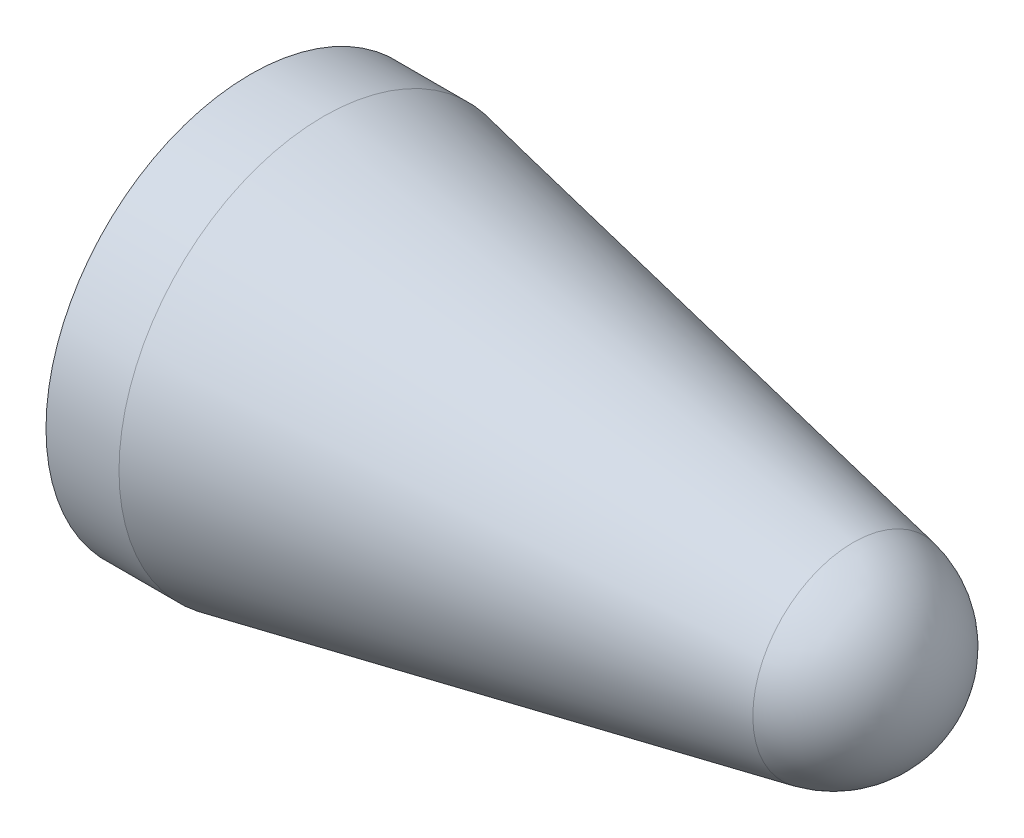
SolidWorks part; units mm, degrees
ref_plane "Front" through (0, 0, 0) normal (0, 0, 1) x (1, 0, 0)
ref_plane "Top" through (0, 0, 0) normal (0, 1, 0) x (1, 0, 0)
ref_plane "Right" through (0, 0, 0) normal (1, 0, 0) x (0, 0, -1)
sketch "Sketch1" plane through (0, 0, 0) normal (0, 0, 1) x (1, 0, 0)
  line L0 (-2, 0) -> (33, 0) construction
  line L1 (-2, 13) -> (34.1581, 5.8872)
  line L2 (-15, 1.7725) -> (-5, 11.953) construction
  line L4 (-15, 0) -> (-14, 0) construction
  line L9 (-15, 0) -> (-15, 1.7725) construction
  line L10 (-24, 16) -> (-24, 20)
  line L12 (-15, 0) -> (-17, 0) construction
  line L14 (-24, 16) -> (-17.2505, 16)
  line L25 (-14, 0) -> (-13, 0) construction
  line L26 (-13, 0) -> (-12, 0) construction
  line L27 (-12, 0) -> (-11, 0) construction
  line L28 (-11, 0) -> (-10, 0) construction
  line L29 (-10, 0) -> (-9, 0) construction
  line L30 (-14, 0) -> (-14, 2.7905) construction
  line L31 (-13, 0) -> (-13, 3.8085) construction
  line L32 (-17, 0) -> (-17, 12.25) construction
  line L33 (-12, 0) -> (-12, 4.8265) construction
  line L34 (34.9302, 9.812) -> (-16.8608, 20)
  line L35 (-11, 0) -> (-11, 5.8445) construction
  line L36 (-10, 0) -> (-10, 6.8625) construction
  line L37 (-15, 0) -> (-2, 0) construction
  line L38 (-9, 0) -> (-9, 7.881) construction
  line L39 (-9, 0) -> (-8, 0) construction
  line L40 (-8, 0) -> (-7, 0) construction
  line L41 (-7, 0) -> (-6, 0) construction
  line L42 (-8, 0) -> (-8, 8.8945) construction
  line L43 (-2, 0) -> (-2, 13) construction
  line L44 (-7, 0) -> (-7, 9.917) construction
  line L46 (-6, 0) -> (-6, 10.935) construction
  line L47 (-6, 0) -> (-5, 0) construction
  line L48 (-5, 0) -> (-5, 11.953) construction
  line L50 (5, 0) -> (5, 21) construction
  line L52 (-5, 11.953) -> (-2, 15.0071) construction
  line L53 (-2, 15.0071) -> (-2, 13) construction
  line L54 (-15, 0) -> (-15, 2.501) construction
  line L55 (-5, 0) -> (-5, 21.231) construction
  line L56 (-5, 21.231) -> (-15, 2.501) construction
  line L57 (-3.7157, 13.3375) -> (-15, 13.3375) construction
  line L58 (-15, 13.3375) -> (-15, 2.501) construction
  line L59 (-8.6917, 14.3164) -> (-15, 14.3164) construction
  line L60 (-15, 14.3164) -> (-15, 13.3375) construction
  line L62 (-2, 13) -> (-17.2505, 16)
  line L63 (-17, 12.25) -> (1.8126, 12.25) construction
  line L64 (-17, 12.25) -> (-17, 15.9507) construction
  line L65 (-24, 20) -> (-16.8608, 20)
  line L66 (39, 0) -> (43, 0)
  arc A8 (39, 0) -> (34.1581, 5.8872) centre (33, 0) ccw
  arc A9 (43, 0) -> (34.9302, 9.812) centre (33, 0) ccw
revolve "Revolve1" add sketch "Sketch1" angle 360 about L66
